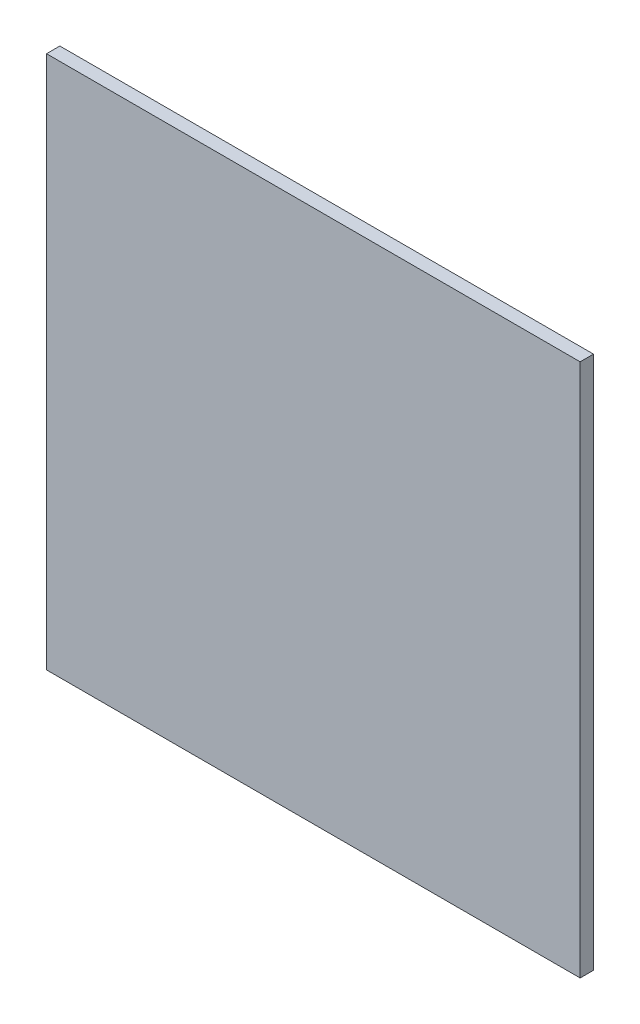
SolidWorks part; units mm, degrees
ref_plane "Front Plane" through (0, 0, 0) normal (0, 0, 1) x (1, 0, 0)
ref_plane "Top Plane" through (0, 0, 0) normal (0, 1, 0) x (1, 0, 0)
ref_plane "Right Plane" through (0, 0, 0) normal (1, 0, 0) x (0, 0, -1)
sketch "Sketch1" plane through (0, 0, 0) normal (0, 0, 1) x (1, 0, 0)
  line L1 (0, 0) -> (400, 0)
  line L2 (0, 0) -> (0, 400)
  line L3 (0, 400) -> (400, 400)
  line L4 (400, 0) -> (400, 400)
  dimension "D1" = 400
  dimension "D2" = 400
extrude "Boss-Extrude1" add sketch "Sketch1" along normal blind 10 contours L3 L4 L1 L2
sketch "Sketch2" plane through (0, 0, 10) normal (0, 0, 1) x (1, 0, 0)
  line L5 (0, 200) -> (50, 200) construction
  line L6 (0, 0) -> (0, 400) construction
  circle A1 centre (55, 200) radius 5
  dimension "D3" = 10
  dimension "D4" = 50
sketch "Sketch4" plane through (0, 0, 10) normal (0, 0, 1) x (1, 0, 0)
  line L0 (400, 200) -> (350.0001, 200) construction
  line L1 (400, 0) -> (400, 400) construction
  line L2 (345.0002, 199.9663) -> (172.0002, 199.9663) construction
  circle A0 centre (345.0002, 199.9663) radius 5
  circle A1 centre (172.0002, 199.9663) radius 5
  point P7 (400, 200)
  dimension "D2" = 10
  dimension "D3" = 173
  dimension "D1" = 54.9998
